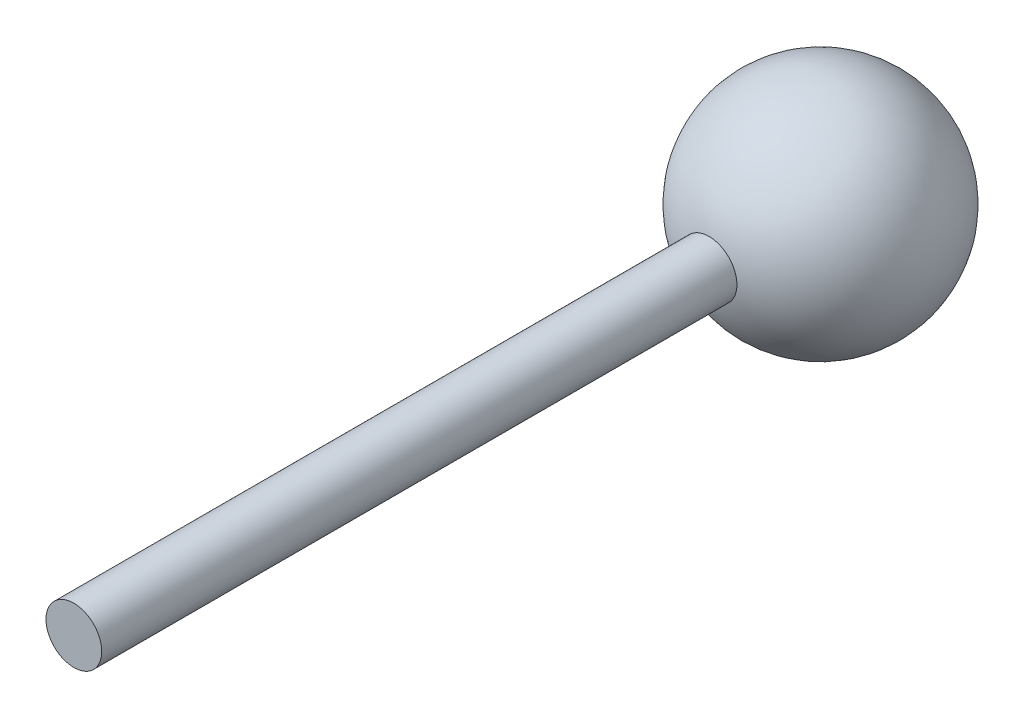
SolidWorks part; units mm, degrees
ref_plane "Front Plane" through (0, 0, 0) normal (0, 0, 1) x (1, 0, 0)
ref_plane "Top Plane" through (0, 0, 0) normal (0, 1, 0) x (1, 0, 0)
ref_plane "Right Plane" through (0, 0, 0) normal (1, 0, 0) x (0, 0, -1)
sketch "Sketch1" plane through (0, 0, 0) normal (0, 0, 1) x (1, 0, 0)
  line L0 (-10, 0) -> (10, 0) construction
  line L1 (10, 0) -> (-10, 0)
  arc A0 (10, 0) -> (-10, 0) centre (0, 0) cw
  dimension "D1" = 20
revolve "Revolve1" add sketch "Sketch1" angle 360 about L0
ref_plane "Plane1" through (0, 0, 10) normal (0, 0, 1) x (1, 0, 0)
sketch "Sketch3" plane through (0, 0, 10) normal (0, 0, 1) x (1, 0, 0)
  line L1 (-2.5, -2.5) -> (2.5, -2.5)
  line L2 (-2.5, -2.5) -> (-2.5, 2.5)
  line L3 (-2.5, 2.5) -> (2.5, 2.5)
  line L4 (2.5, -2.5) -> (2.5, 2.5)
  line L5 (-2.5, -2.5) -> (2.5, 2.5) construction
  line L6 (-2.5, 2.5) -> (2.5, -2.5) construction
  circle A0 centre (0, 0) radius 2.5
  point P0 (0, 0)
  dimension "D1" = 5
extrude "Boss-Extrude2" add sketch "Sketch3" along normal blind 57 separate body contours A0
